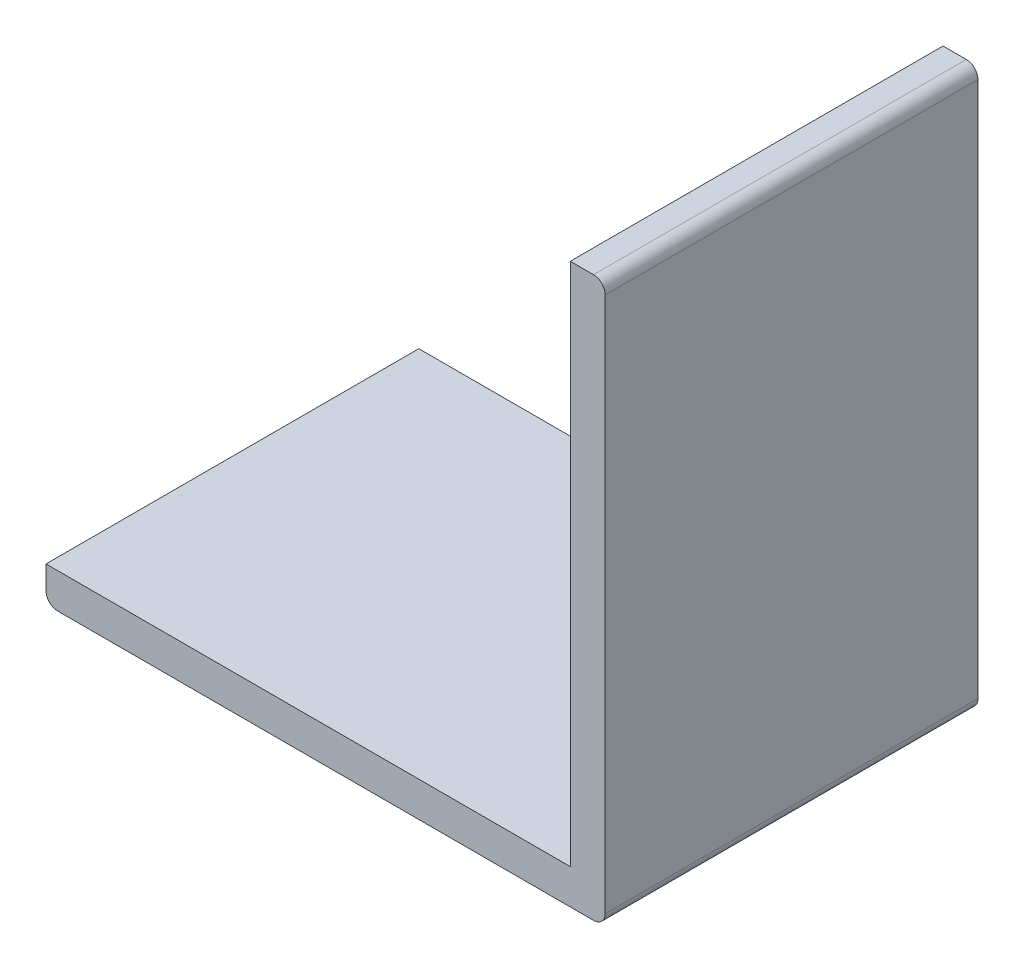
SolidWorks part; units mm, degrees
material "Alloy Steel"
ref_plane "Front Plane" through (0, 0, 0) normal (0, 0, 1) x (1, 0, 0)
ref_plane "Top Plane" through (0, 0, 0) normal (0, 1, 0) x (1, 0, 0)
ref_plane "Right Plane" through (0, 0, 0) normal (1, 0, 0) x (0, 0, -1)
sketch "Sketch1" plane through (0, 0, 0) normal (0, 0, 1) x (1, 0, 0)
  line L1 (-47.566, -5168.8161) -> (-47.566, 0)
  line L3 (-53.408, -5168.8161) -> (-53.408, 0)
  line L8 (0, -2736.808) -> (-101.6, -2736.808)
  line L9 (-101.6, -2736.808) -> (-101.6, -5168.8161)
  line L10 (-101.6, -5168.8161) -> (0, -5168.8161)
  line L11 (0, -5168.8161) -> (0, -2736.808)
  line L16 (-2102.3172, -5115.408) -> (-2102.3172, -5217.008)
  line L17 (-2102.3172, -5217.008) -> (-101.6, -5217.008)
  line L18 (-101.6, -5217.008) -> (-101.6, -5115.408)
  line L19 (-101.6, -5115.408) -> (-2102.3172, -5115.408)
  line L21 (-2102.0067, -5168.8161) -> (-101.6, -5168.8161)
  line L23 (-2102.0067, -5162.9741) -> (-101.6, -5162.9741)
  line L24 (-190.441, -5168.8161) -> (-190.441, -5175.1661)
  line L25 (-187.266, -5178.3411) -> (-41.216, -5178.3411)
  line L26 (-38.041, -5175.1661) -> (-38.041, -5029.1161)
  line L27 (-41.216, -5025.9411) -> (-47.566, -5025.9411)
  line L28 (-47.566, -5025.9411) -> (-47.566, -5168.8161)
  line L29 (-47.566, -5168.8161) -> (-190.441, -5168.8161)
  line L30 (-101.6, -5168.8161) -> (-190.441, -5168.8161)
  line L31 (-101.6, -5168.8161) -> (-190.441, -5168.8161)
  arc A0 (-41.216, -5025.9411) -> (-38.041, -5029.1161) centre (-41.216, -5029.1161) cw
  arc A1 (-190.441, -5175.1661) -> (-187.266, -5178.3411) centre (-187.266, -5175.1661) ccw
  arc A2 (-38.041, -5175.1661) -> (-41.216, -5178.3411) centre (-41.216, -5175.1661) cw
  point P17 (-44.391, -5025.9411)
  dimension "D7" = 3.175
  dimension "D3" = 9.525
  dimension "D4" = 9.525
  dimension "D5" = 152.4
  dimension "D6" = 152.4
extrude "Boss-Extrude1" add sketch "Sketch1" against normal blind 101.6 contours L24 A1 L25 L18 L21 | A2 L26 L10 L18 L25 | A0 L27 L1 L10 L26
